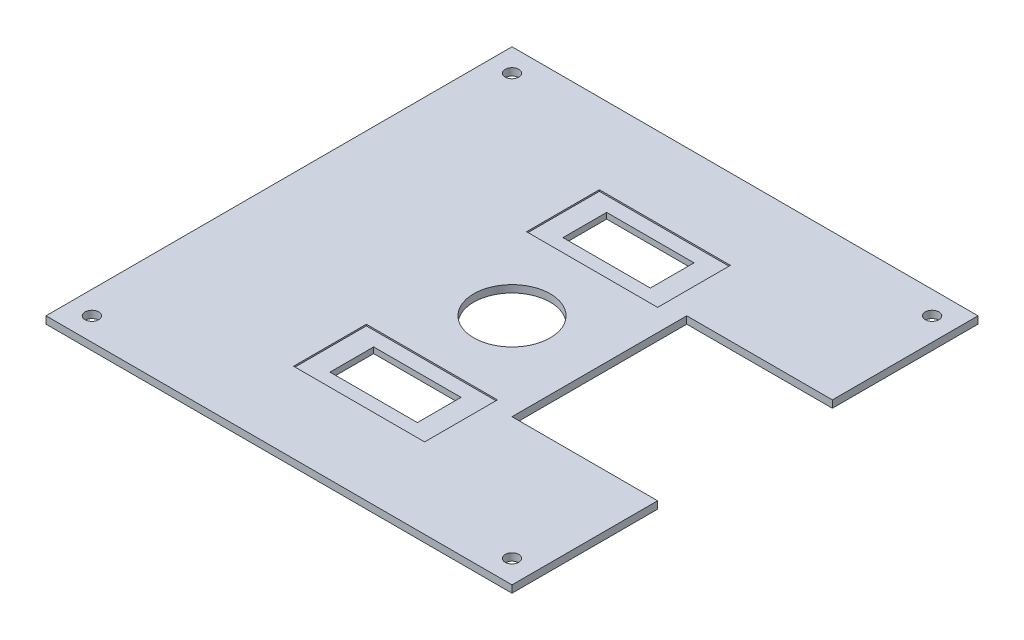
SolidWorks part; units mm, degrees
material "6061-T6 (SS)"
ref_plane "Front Plane" through (0, 0, 0) normal (0, 0, 1) x (1, 0, 0)
ref_plane "Top Plane" through (0, 0, 0) normal (0, 1, 0) x (1, 0, 0)
ref_plane "Right Plane" through (0, 0, 0) normal (1, 0, 0) x (0, 0, -1)
sketch "Sketch1" plane through (0, 0, 0) normal (0, 1, 0) x (1, 0, 0)
  line L1 (-101.6, -101.6) -> (101.6, -101.6)
  line L2 (-101.6, -101.6) -> (-101.6, 101.6)
  line L3 (-101.6, 101.6) -> (101.6, 101.6)
  line L4 (101.6, -101.6) -> (101.6, 101.6)
  line L5 (-101.6, -101.6) -> (101.6, 101.6) construction
  line L6 (-101.6, 101.6) -> (101.6, -101.6) construction
  circle A0 centre (0, 0) radius 16.6687
  point P0 (0, 0)
  dimension "D3" = 33.3375
  dimension "D1" = 203.2
  dimension "D2" = 203.2
extrude "Boss-Extrude1" add sketch "Sketch1" along normal blind 3.175
sketch "Sketch2" plane through (0, 3.175, 0) normal (0, 1, 0) x (1, 0, 0)
  line L0 (-163.7555, 0) -> (163.7555, 0) construction
  line L1 (38.1, -38.1) -> (38.1, 38.1)
  line L2 (101.6, -101.6) -> (101.6, 101.6) construction
  line L3 (38.1, 38.1) -> (101.6, 38.1)
  line L4 (101.6, 38.1) -> (101.6, -38.1)
  line L5 (101.6, -38.1) -> (38.1, -38.1)
  point P5 (0, 0)
  point P9 (38.1, 0)
  dimension "D1" = 76.2
  dimension "D2" = 63.5
extrude "Cut-Extrude1" cut sketch "Sketch2" against normal blind 3.175
sketch "Sketch3" plane through (0, 3.175, 0) normal (0, 1, 0) x (1, 0, 0)
  line L0 (-193.7836, 0) -> (193.7836, 0) construction
  line L1 (0, -142.0379) -> (0, 142.0379) construction
  line L2 (28.575, -34.925) -> (28.575, -66.675)
  line L3 (-28.575, 34.925) -> (28.575, 34.925)
  line L4 (-28.575, 34.925) -> (-28.575, 66.675)
  line L5 (-28.575, 66.675) -> (28.575, 66.675)
  line L6 (28.575, 34.925) -> (28.575, 66.675)
  line L7 (-28.575, 34.925) -> (28.575, 66.675) construction
  line L8 (-28.575, 66.675) -> (28.575, 34.925) construction
  line L9 (-28.575, -34.925) -> (28.575, -34.925)
  line L10 (-28.575, -34.925) -> (-28.575, -66.675)
  line L11 (-28.575, -66.675) -> (28.575, -66.675)
  point P0 (0, 50.8)
  point P4 (0, 0)
  point P8 (0, 0)
  dimension "D1" = 57.15
  dimension "D2" = 31.75
  dimension "D3" = 50.8
extrude "Cut-Extrude2" cut sketch "Sketch3" against normal blind 0.635
sketch "Sketch4" plane through (0, 3.175, 0) normal (0, 1, 0) x (1, 0, 0)
  line L0 (-156.5198, 0) -> (156.5198, 0) construction
  line L1 (0, -139.5054) -> (0, 139.5054) construction
  line L2 (19.05, -41.275) -> (19.05, -60.325)
  line L3 (-19.05, 41.275) -> (19.05, 41.275)
  line L4 (-19.05, 41.275) -> (-19.05, 60.325)
  line L5 (-19.05, 60.325) -> (19.05, 60.325)
  line L6 (19.05, 41.275) -> (19.05, 60.325)
  line L7 (-19.05, 41.275) -> (19.05, 60.325) construction
  line L8 (-19.05, 60.325) -> (19.05, 41.275) construction
  line L9 (-19.05, -41.275) -> (19.05, -41.275)
  line L10 (-19.05, -41.275) -> (-19.05, -60.325)
  line L11 (-19.05, -60.325) -> (19.05, -60.325)
  point P0 (0, 50.8)
  point P5 (0, 0)
  point P9 (0, 0)
  dimension "D1" = 38.1
  dimension "D2" = 50.8
  dimension "D3" = 19.05
extrude "Cut-Extrude3" cut sketch "Sketch4" against normal blind 3.175
sketch "Sketch5" plane through (0, 3.175, 0) normal (0, 1, 0) x (1, 0, 0)
  circle A0 centre (0, 0) radius 75.565
  circle A1 centre (0, 0) radius 85.725
  dimension "D1" = 151.13
  dimension "D2" = 171.45
sketch "Sketch6" plane through (0, 3.175, 0) normal (0, 1, 0) x (1, 0, 0)
  line L0 (-166.7318, 0) -> (166.7318, 0) construction
  line L1 (0, -120.7082) -> (0, 120.7082) construction
  line L2 (-101.6, 101.6) -> (-101.6, -101.6) construction
  line L3 (101.6, 101.6) -> (-101.6, 101.6) construction
  circle A0 centre (-91.6, 91.6) radius 2.9769
  circle A1 centre (91.6, 91.6) radius 2.9769
  circle A2 centre (91.6, -91.6) radius 2.9769
  circle A3 centre (-91.6, -91.6) radius 2.9769
  point P5 (0, 0)
  point P9 (0, 0)
  dimension "D1" = 5.9538
  dimension "D2" = 10
  dimension "D3" = 10
extrude "Cut-Extrude5" cut sketch "Sketch6" against normal blind 38.1
sketch "Sketch7" plane through (0, 3.175, 0) normal (0, 1, 0) x (1, 0, 0)
  line L0 (-101.6, -101.6) -> (101.6, 101.6) construction
  line L1 (101.6, -101.6) -> (-101.6, 101.6) construction
  point P5 (0, 0)
  point P10 (0, 0)
sketch "Sketch8" plane through (0, 3.175, 0) normal (0, 1, 0) x (1, 0, 0)
  circle A0 centre (0, 0) radius 77.0255 construction
  circle A1 centre (0, 0) radius 84.201 construction
  circle A2 centre (0, 0) radius 76.2
  circle A3 centre (0, 0) radius 85.725
  dimension "D1" = 154.051
  dimension "D2" = 168.402
  dimension "D3" = 152.4
  dimension "D4" = 171.45
extrude "Cut-Extrude6" [suppressed] cut sketch "Sketch8" against normal blind 0.7937
